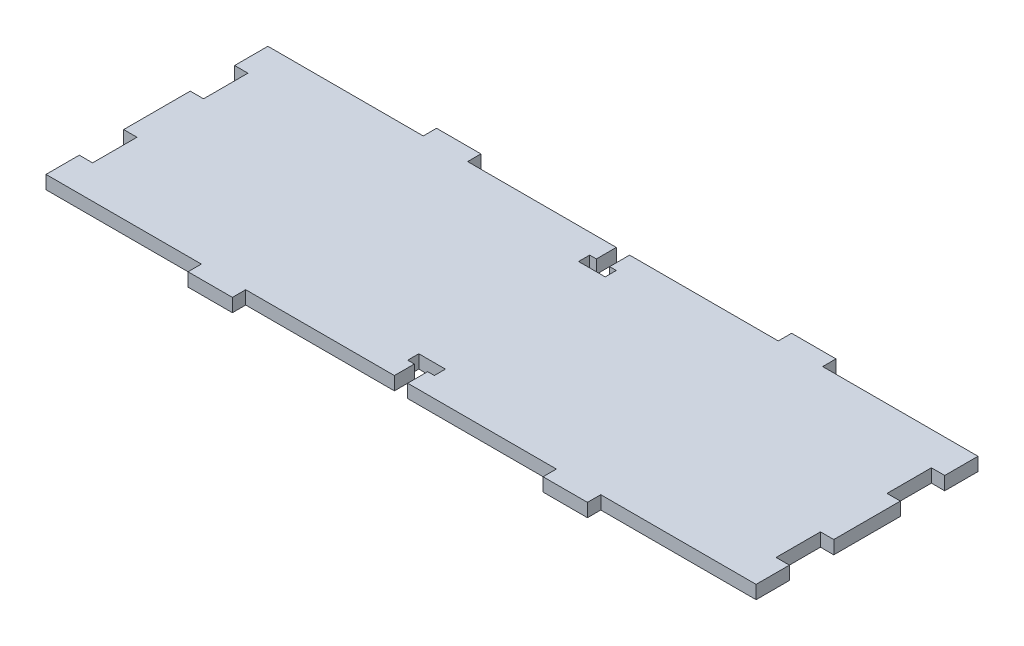
SolidWorks part; units mm, degrees
ref_plane "Front Plane" through (0, 0, 0) normal (0, 0, 1) x (1, 0, 0)
ref_plane "Top Plane" through (0, 0, 0) normal (0, 1, 0) x (1, 0, 0)
ref_plane "Right Plane" through (0, 0, 0) normal (1, 0, 0) x (0, 0, -1)
sketch "Sketch3" plane through (0, 0, 0) normal (0, 1, 0) x (1, 0, 0)
  line L0 (0, 66.6216) -> (0, -68.7838) construction
  line L1 (-104.3243, 0) -> (111.6216, 0) construction
  line L3 (-80, 28) -> (80, 28)
  line L4 (-80, 28) -> (-80, -28)
  line L5 (-80, -28) -> (80, -28)
  line L6 (80, 28) -> (80, -28)
  line L7 (-80, 28) -> (80, -28) construction
  line L8 (-80, -28) -> (80, 28) construction
  point P1 (0, 0)
  dimension "D1" = 56
  dimension "D2" = 160
extrude "Boss-Extrude1" add sketch "Sketch3" along normal blind 3
sketch "Sketch4" plane through (0, 3, 0) normal (0, 1, 0) x (1, 0, 0)
  line L0 (0, 16.1567) -> (0, -10.6496) construction
  line L1 (-38.2504, 0) -> (41.6071, 0) construction
  line L2 (-80, 28) -> (-80, -28) construction
  line L3 (-80, 17.5) -> (-77, 17.5)
  line L4 (-80, 17.5) -> (-80, 7.5)
  line L5 (-80, 7.5) -> (-77, 7.5)
  line L6 (-77, 17.5) -> (-77, 7.5)
  line L7 (-35, 28) -> (-35, 25)
  line L8 (-80, 28) -> (-45, 28)
  line L9 (-80, 28) -> (-80, 25)
  line L10 (-80, 25) -> (-45, 25)
  line L11 (-45, 28) -> (-45, 25)
  line L12 (80, 28) -> (-80, 28) construction
  line L13 (-35, 25) -> (-1.5, 25)
  line L14 (-1.5, 25) -> (-1.5, 20.5)
  line L15 (-1.5, 20.5) -> (-3, 20.5)
  line L16 (-3, 20.5) -> (-3, 18)
  line L17 (-3, 18) -> (3, 18)
  line L18 (3, 18) -> (3, 20.5)
  line L19 (3, 20.5) -> (1.5, 20.5)
  line L20 (1.5, 20.5) -> (1.5, 25)
  line L21 (1.5, 25) -> (35, 25)
  line L22 (35, 25) -> (35, 28)
  line L23 (35, 28) -> (-35, 28)
  line L24 (45, 28) -> (45, 25)
  line L25 (80, 25) -> (45, 25)
  line L26 (80, 28) -> (80, 25)
  line L27 (80, 28) -> (45, 28)
  line L28 (77, 17.5) -> (77, 7.5)
  line L29 (80, 7.5) -> (77, 7.5)
  line L30 (80, 17.5) -> (80, 7.5)
  line L31 (80, 17.5) -> (77, 17.5)
  line L32 (80, -17.5) -> (77, -17.5)
  line L33 (80, -17.5) -> (80, -7.5)
  line L34 (80, -7.5) -> (77, -7.5)
  line L35 (77, -17.5) -> (77, -7.5)
  line L36 (80, -28) -> (45, -28)
  line L37 (80, -28) -> (80, -25)
  line L38 (80, -25) -> (45, -25)
  line L39 (45, -28) -> (45, -25)
  line L40 (35, -28) -> (-35, -28)
  line L41 (35, -25) -> (35, -28)
  line L42 (1.5, -25) -> (35, -25)
  line L43 (1.5, -20.5) -> (1.5, -25)
  line L44 (3, -20.5) -> (1.5, -20.5)
  line L45 (3, -18) -> (3, -20.5)
  line L46 (-3, -18) -> (3, -18)
  line L47 (-3, -20.5) -> (-3, -18)
  line L48 (-1.5, -20.5) -> (-3, -20.5)
  line L49 (-1.5, -25) -> (-1.5, -20.5)
  line L50 (-35, -25) -> (-1.5, -25)
  line L51 (-45, -28) -> (-45, -25)
  line L52 (-80, -25) -> (-45, -25)
  line L53 (-80, -28) -> (-80, -25)
  line L54 (-80, -28) -> (-45, -28)
  line L55 (-35, -28) -> (-35, -25)
  line L56 (-77, -17.5) -> (-77, -7.5)
  line L57 (-80, -7.5) -> (-77, -7.5)
  line L58 (-80, -17.5) -> (-80, -7.5)
  line L59 (-80, -17.5) -> (-77, -17.5)
  dimension "D1" = 10
  dimension "D2" = 7.5
  dimension "D3" = 3
  dimension "D4" = 3
  dimension "D5" = 45
  dimension "D6" = 35
  dimension "D7" = 35
  dimension "D8" = 3
  dimension "D9" = 3
  dimension "D10" = 10
  dimension "D11" = 2.5
  dimension "D12" = 2.5
  dimension "D13" = 1.5
  dimension "D14" = 1.5
  dimension "D15" = 3
  dimension "D16" = 1.5
extrude "Cut-Extrude1" cut sketch "Sketch4" against normal through all
